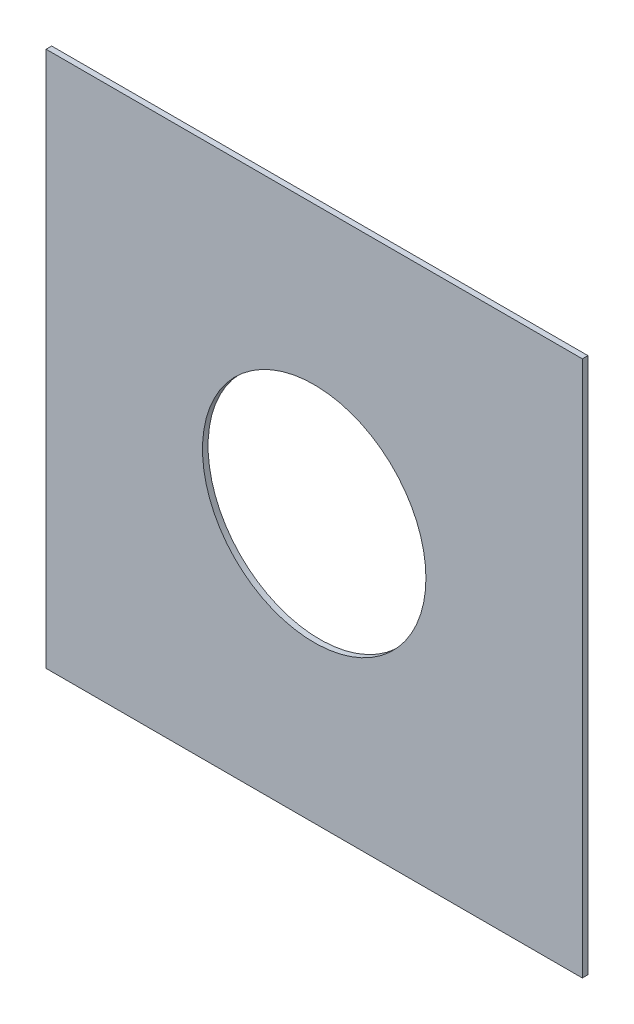
SolidWorks part; units mm, degrees
material "Glass"
ref_plane "Front Plane" through (0, 0, 0) normal (0, 0, 1) x (1, 0, 0)
ref_plane "Top Plane" through (0, 0, 0) normal (0, 1, 0) x (1, 0, 0)
ref_plane "Right Plane" through (0, 0, 0) normal (1, 0, 0) x (0, 0, -1)
sketch "Sketch1" plane through (0, 0, 0) normal (0, 0, 1) x (1, 0, 0)
  line L1 (-152.4, -152.4) -> (152.4, -152.4)
  line L2 (-152.4, -152.4) -> (-152.4, 152.4)
  line L3 (-152.4, 152.4) -> (152.4, 152.4)
  line L4 (152.4, -152.4) -> (152.4, 152.4)
  line L5 (-152.4, -152.4) -> (152.4, 152.4) construction
  line L6 (-152.4, 152.4) -> (152.4, -152.4) construction
  circle A0 centre (0, 0) radius 63.5
  point P0 (0, 0)
  dimension "D1" = 127
  dimension "D2" = 304.8
  dimension "D3" = 304.8
extrude "Boss-Extrude1" add sketch "Sketch1" along normal blind 3.175
